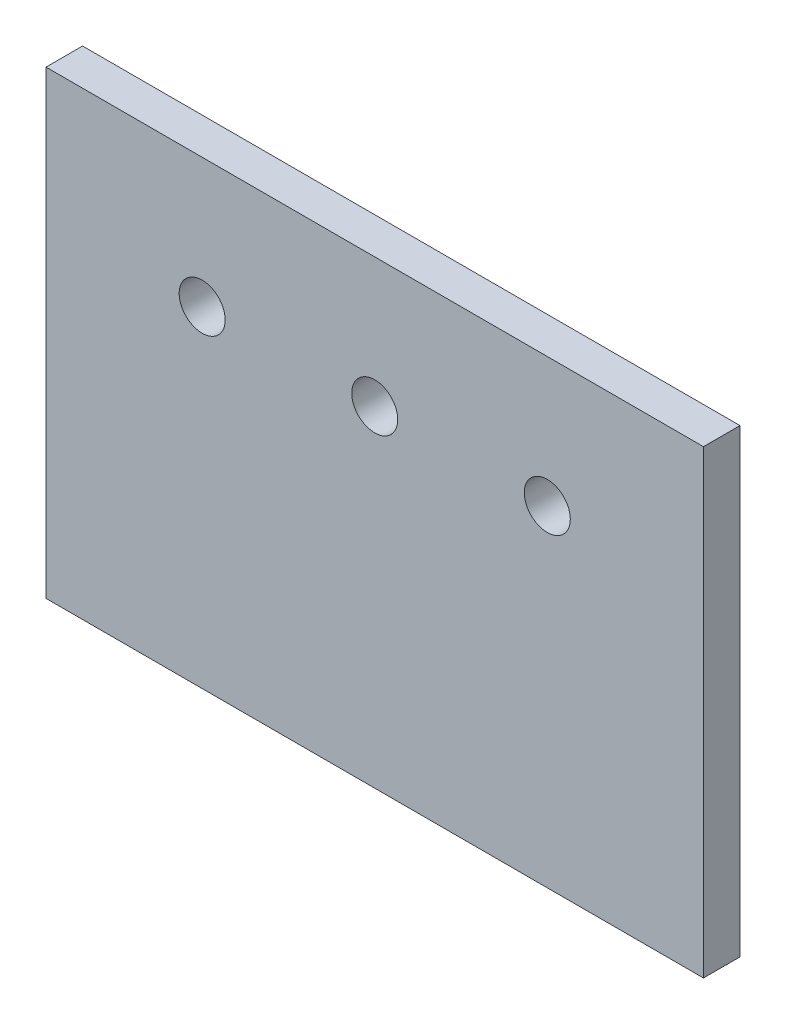
SolidWorks part; units mm, degrees
ref_plane "Front Plane" through (0, 0, 0) normal (0, 0, 1) x (1, 0, 0)
ref_plane "Top Plane" through (0, 0, 0) normal (0, 1, 0) x (1, 0, 0)
ref_plane "Right Plane" through (0, 0, 0) normal (1, 0, 0) x (0, 0, -1)
sketch "Sketch1" plane through (0, 0, 0) normal (0, 0, 1) x (1, 0, 0)
  line L1 (0, 0) -> (114.3, 0)
  line L2 (0, 0) -> (0, -80)
  line L3 (0, -80) -> (114.3, -80)
  line L4 (114.3, 0) -> (114.3, -80)
  circle A0 centre (57.15, -22.5) radius 4
  circle A1 centre (27.15, -22.5) radius 4
  circle A2 centre (87.15, -22.5) radius 4
  dimension "D3" = 57.15
  dimension "D5" = 30
  dimension "D6" = 8
  dimension "D7" = 30
  dimension "D4" = 22.5
  dimension "D1" = 80
  dimension "D2" = 114.3
extrude "Boss-Extrude1" add sketch "Sketch1" along normal blind 6.35
